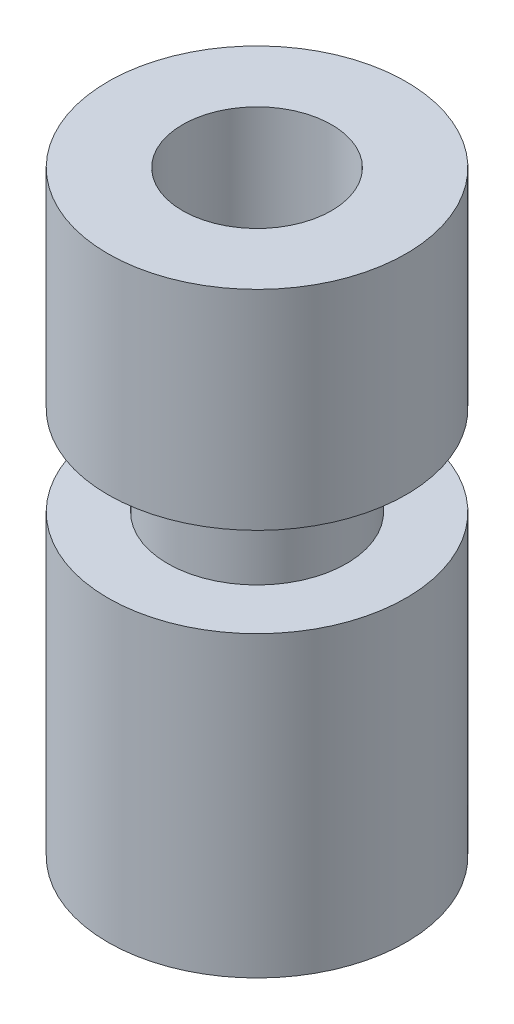
SolidWorks part; units mm, degrees
material "Stainless Steel (ferritic)"
ref_plane "Front Plane" through (0, 0, 0) normal (0, 0, 1) x (1, 0, 0)
ref_plane "Top Plane" through (0, 0, 0) normal (0, 1, 0) x (1, 0, 0)
ref_plane "Right Plane" through (0, 0, 0) normal (1, 0, 0) x (0, 0, -1)
sketch "Sketch1" plane through (0, 0, 0) normal (0, 1, 0) x (1, 0, 0)
  circle A0 centre (0, 0) radius 2.5
  dimension "D1" = 5
extrude "Boss-Extrude1" add sketch "Sketch1" along normal blind 5
sketch "Sketch2" plane through (0, 5, 0) normal (0, 1, 0) x (1, 0, 0)
  circle A0 centre (0, 0) radius 1.5
  dimension "D1" = 3
extrude "Boss-Extrude2" add sketch "Sketch2" along normal blind 1.5
sketch "Sketch3" plane through (0, 6.5, 0) normal (0, 1, 0) x (1, 0, 0)
  circle A0 centre (0, 0) radius 2.5
  dimension "D1" = 5
extrude "Boss-Extrude3" add sketch "Sketch3" along normal blind 3.5
sketch "Sketch4" plane through (0, 10, 0) normal (0, 1, 0) x (1, 0, 0)
  circle A0 centre (0, 0) radius 1.25
  dimension "D1" = 2.5
extrude "Cut-Extrude1" cut sketch "Sketch4" against normal blind 2
